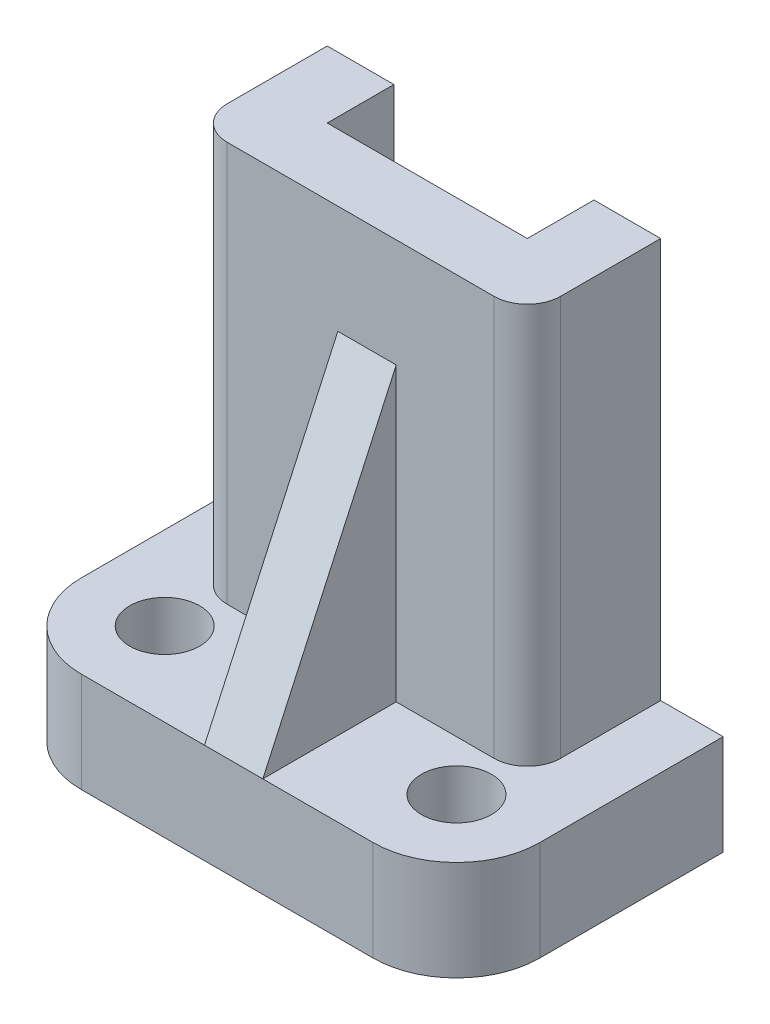
SolidWorks part; units mm, degrees
ref_plane "Ön Düzlem" through (0, 0, 0) normal (0, 0, 1) x (1, 0, 0)
ref_plane "Üst Düzlem" through (0, 0, 0) normal (0, 1, 0) x (1, 0, 0)
ref_plane "Sağ Düzlem" through (0, 0, 0) normal (1, 0, 0) x (0, 0, -1)
sketch "Çizim1" plane through (0, 0, 0) normal (0, 0, 1) x (1, 0, 0)
  line L21 (0, 0) -> (-40, 0)
  line L22 (0, 0) -> (0, 48)
  line L23 (0, 48) -> (-40, 48)
  line L24 (-40, 0) -> (-40, 48)
  dimension "D1" = 48
  dimension "D2" = 40
extrude "Yükseklik-Ekstrüzyon1" add sketch "Çizim1" along normal blind 16
fillet "Radyus4" radius 4 2 edges at (-40, 24, 16) (0, 24, 16)
sketch "Çizim5" plane through (0, 48, 0) normal (0, 1, 0) x (1, 0, 0)
  line L0 (0, 0) -> (-40, 0) construction
  line L5 (-8, -8) -> (-32, -8)
  line L6 (-8, -8) -> (-8, 0)
  line L7 (-8, 0) -> (-32, 0)
  line L8 (-32, -8) -> (-32, 0)
  line L9 (-8, -8) -> (-32, 0) construction
  line L10 (-8, 0) -> (-32, -8) construction
  point P0 (-20, -4)
  point P5 (-20, -4.0297)
  dimension "D1" = 0
  dimension "D2" = 8
  dimension "D3" = 24
extrude "Kes-Ekstrüzyon1" cut sketch "Çizim5" against normal blind 59
sketch "Çizim6" plane through (0, 0, 0) normal (0, -1, 0) x (1, 0, 0)
  line L6 (7.5, 0) -> (-47.5, 0)
  line L7 (7.5, 0) -> (7.5, 32)
  line L8 (7.5, 32) -> (-47.5, 32)
  line L9 (-47.5, 0) -> (-47.5, 32)
  dimension "D1" = 55
  dimension "D2" = 32
  dimension "D3" = 7.5
  dimension "D4" = 7.5
extrude "Yükseklik-Ekstrüzyon4" add sketch "Çizim6" along normal blind 12
fillet "Radyus7" radius 10 2 edges at (7.5, -6, 32) (-47.5, -6, 32)
sketch "Çizim9" plane through (0, -12, 0) normal (0, -1, 0) x (1, 0, 0)
  circle A0 centre (-37.5, 22) radius 4.2
  circle A1 centre (-2.5, 22) radius 4.2
  dimension "D1" = 8.4
  dimension "D2" = 8.4
extrude "Kes-Ekstrüzyon2" cut sketch "Çizim9" against normal blind 21
sketch "Çizim10" plane through (0, 0, 16) normal (0, 0, 1) x (1, 0, 0)
  line L1 (-15.7276, 35) -> (-22.7276, 35)
  line L2 (-15.7276, 35) -> (-15.7276, 0)
  line L3 (-15.7276, 0) -> (-22.7276, 0)
  line L4 (-22.7276, 35) -> (-22.7276, 0)
  point P0 (-19.2276, 17.5)
  point P5 (-20, 18)
extrude "Yükseklik-Ekstrüzyon5" add sketch "Çizim10" along normal blind 16
sketch "Çizim11" plane through (-15.7276, 0, 0) normal (1, 0, 0) x (0, 0, -1)
  line L0 (-16, 35) -> (-32, 0)
  line L1 (-32, 0) -> (-32, 35)
  line L2 (-32, 35) -> (-16, 35)
extrude "Kes-Ekstrüzyon3" cut sketch "Çizim11" against normal blind 16
